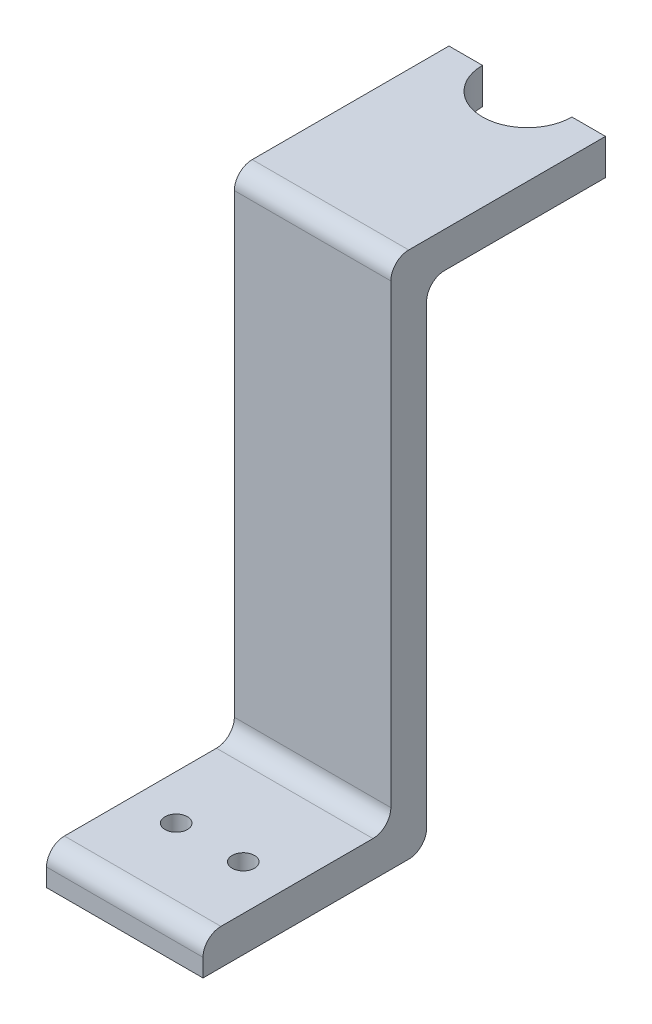
SolidWorks part; units mm, degrees
ref_plane "Front Plane" through (0, 0, 0) normal (0, 0, 1) x (1, 0, 0)
ref_plane "Top Plane" through (0, 0, 0) normal (0, 1, 0) x (1, 0, 0)
ref_plane "Right Plane" through (0, 0, 0) normal (1, 0, 0) x (0, 0, -1)
sketch "Sketch1" plane through (0, 0, 0) normal (1, 0, 0) x (0, 0, -1)
  line L0 (0, 0) -> (0, 4)
  line L1 (4, 8) -> (38, 8)
  line L2 (42, 12) -> (42, 114)
  line L3 (90, 110) -> (90, 118)
  line L4 (0, 0) -> (46, 0)
  line L5 (50, 4) -> (50, 106)
  line L6 (54, 110) -> (90, 110)
  line L7 (90, 118) -> (46, 118)
  arc A0 (46, 118) -> (42, 114) centre (46, 114) ccw
  arc A1 (54, 110) -> (50, 106) centre (54, 106) ccw
  arc A2 (46, 0) -> (50, 4) centre (46, 4) ccw
  arc A3 (42, 12) -> (38, 8) centre (38, 12) cw
  arc A4 (4, 8) -> (0, 4) centre (4, 4) ccw
  point P11 (42, 118)
  point P14 (50, 110)
  point P17 (50, 0)
  point P20 (42, 8)
  point P23 (0, 8)
  dimension "D7" = 4
  dimension "D1" = 8
  dimension "D2" = 50
  dimension "D3" = 40
  dimension "D4" = 110
  dimension "D5" = 8
  dimension "D6" = 8
extrude "Boss-Extrude1" add sketch "Sketch1" along normal blind 35
sketch "Sketch2" plane through (0, 118, 0) normal (0, 1, 0) x (1, 0, 0)
  line L0 (35, 90) -> (0, 90) construction
  line L1 (17.5, 90) -> (27.5, 90)
  line L2 (27.5, 90) -> (7.5, 90)
  circle A0 centre (17.5, 90) radius 10
extrude "Cut-Extrude1" cut sketch "Sketch2" along direction (0, -1, 0) on the side against the normal blind 10 contours A0
sketch "Sketch3" plane through (0, 8, 0) normal (0, 1, 0) x (1, 0, 0)
  line L0 (0, 38) -> (0, 4) construction
  line L1 (35, 4) -> (0, 4) construction
  circle A0 centre (10, 19) radius 2.5
  circle A1 centre (25, 19) radius 2.5
  dimension "D1" = 5
  dimension "D2" = 5
  dimension "D3" = 10
  dimension "D4" = 15
  dimension "D5" = 15
  dimension "D6" = 15
extrude "Cut-Extrude2" cut sketch "Sketch3" against normal through all
